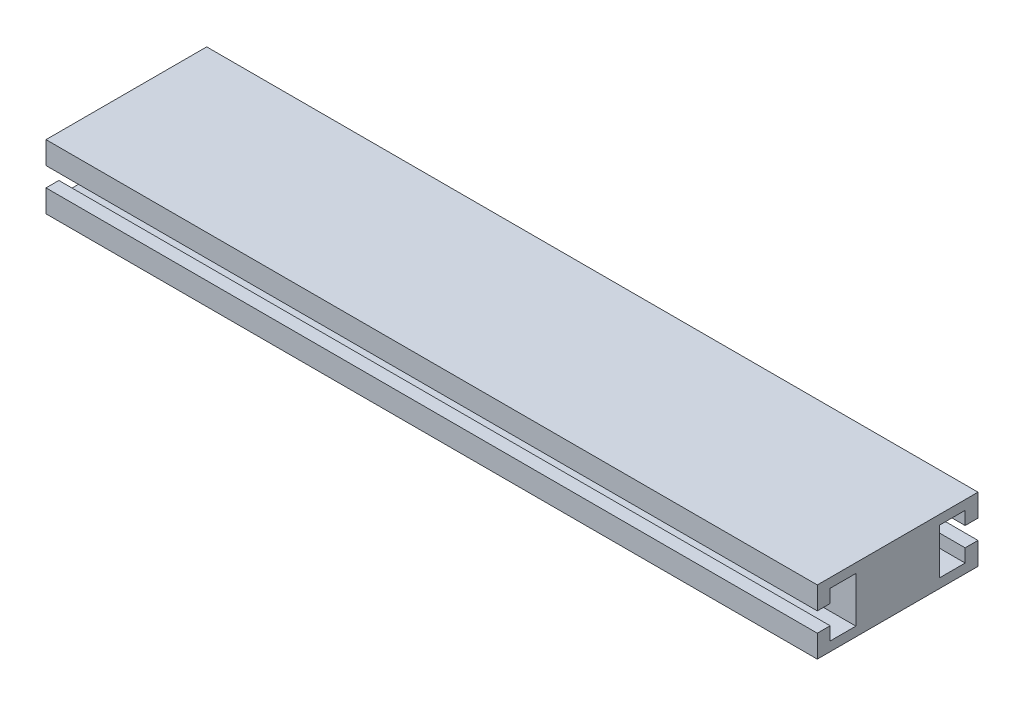
SolidWorks part; units mm, degrees
ref_plane "Front Plane" through (0, 0, 0) normal (0, 0, 1) x (1, 0, 0)
ref_plane "Top Plane" through (0, 0, 0) normal (0, 1, 0) x (1, 0, 0)
ref_plane "Right Plane" through (0, 0, 0) normal (1, 0, 0) x (0, 0, -1)
sketch "Sketch1" plane through (0, 0, 0) normal (0, 1, 0) x (1, 0, 0)
  line L1 (-155.0611, -88.7726) -> (-35.0611, -88.7726)
  line L2 (-155.0611, -88.7726) -> (-155.0611, -63.7726)
  line L3 (-155.0611, -63.7726) -> (-35.0611, -63.7726)
  line L4 (-35.0611, -88.7726) -> (-35.0611, -63.7726)
  dimension "D1" = 120
  dimension "D2" = 25
extrude "Boss-Extrude1" add sketch "Sketch1" along normal blind 10
sketch "Sketch2" plane through (-35.0611, 0, 0) normal (1, 0, 0) x (0, 0, -1)
  line L0 (-63.7726, 6.5) -> (-65.7726, 6.5)
  line L1 (-63.7726, 10) -> (-63.7726, 0) construction
  line L2 (-65.7726, 6.5) -> (-65.7726, 8.55)
  line L3 (-65.7726, 8.55) -> (-69.7726, 8.55)
  line L4 (-69.7726, 8.55) -> (-69.7726, 1.45)
  line L5 (-69.7726, 1.45) -> (-65.7726, 1.45)
  line L6 (-65.7726, 1.45) -> (-65.7726, 3.5)
  line L7 (-65.7726, 3.5) -> (-63.7726, 3.5)
  line L8 (-63.7726, 3.5) -> (-63.7726, 6.5)
  line L9 (-88.7726, 10) -> (-63.7726, 10) construction
  dimension "D1" = 3
  dimension "D2" = 4
  dimension "D3" = 7.1
  dimension "D4" = 2
  dimension "D5" = 2.05
  dimension "D6" = 2
  dimension "D7" = 1.45
extrude "Cut-Extrude1" cut sketch "Sketch2" against normal blind 120
sketch "Sketch3" plane through (-35.0611, 0, 0) normal (1, 0, 0) x (0, 0, -1)
  line L0 (-88.7726, 6.5) -> (-86.7726, 6.5)
  line L1 (-88.7726, 10) -> (-88.7726, 0) construction
  line L2 (-86.7726, 6.5) -> (-86.7726, 8.55)
  line L3 (-86.7726, 8.55) -> (-82.7726, 8.55)
  line L4 (-82.7726, 8.55) -> (-82.7726, 1.45)
  line L5 (-82.7726, 1.45) -> (-86.7726, 1.45)
  line L6 (-86.7726, 1.45) -> (-86.7726, 3.5)
  line L7 (-86.7726, 3.5) -> (-88.7726, 3.5)
  line L8 (-88.7726, 3.5) -> (-88.7726, 6.5)
  line L9 (-88.7726, 0) -> (-63.7726, 0) construction
  dimension "D1" = 7.1
  dimension "D2" = 4
  dimension "D3" = 2
  dimension "D4" = 2.05
  dimension "D5" = 2.05
  dimension "D6" = 2
  dimension "D7" = 1.45
extrude "Cut-Extrude2" cut sketch "Sketch3" against normal blind 120
